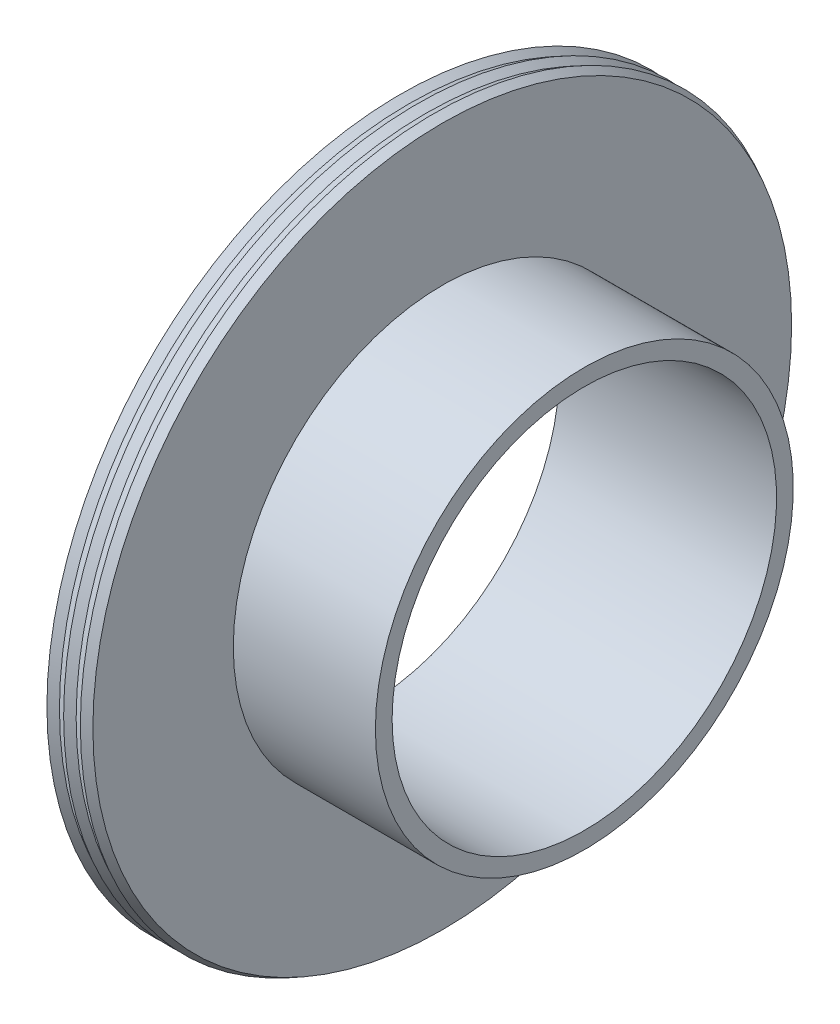
SolidWorks part; units mm, degrees
ref_plane "前视基准面" through (0, 0, 0) normal (0, 0, 1) x (1, 0, 0)
ref_plane "上视基准面" through (0, 0, 0) normal (0, 1, 0) x (1, 0, 0)
ref_plane "右视基准面" through (0, 0, 0) normal (1, 0, 0) x (0, 0, -1)
other "Configuration Table"
sketch "草图1" plane through (0, 0, 0) normal (0, 0, 1) x (1, 0, 0)
  line L0 (-59.6593, 0) -> (89.3294, 0) construction
  line L1 (0, 0) -> (0, 23)
  line L2 (0, 23) -> (26, 23)
  line L3 (26, 23) -> (26, 25)
  line L4 (26, 25) -> (0, 25)
  line L5 (0, 25) -> (0, 23)
  line L6 (0, 0) -> (0, 25)
  line L8 (4, 42.3) -> (9, 42.3)
  line L9 (9, 42.3) -> (9, 25)
  line L10 (9, 25) -> (4, 25)
  line L11 (4, 25) -> (4, 42.3)
  line L13 (4, 42.3) -> (5, 41.8)
  line L14 (5, 41.8) -> (6, 42.3)
  line L15 (6, 42.3) -> (7, 41.8)
  line L16 (7, 41.8) -> (8, 42.3)
  line L17 (8, 42.3) -> (9, 41.8)
  line L19 (9, 41.8) -> (10, 42.3) [skipped]
  dimension "D1" = 23
  dimension "D2" = 2
  dimension "D3" = 26
  dimension "D5" = 17.3
  dimension "D6" = 5
  dimension "D9" = 1
  dimension "D10" = 3
revolve "旋转1" add sketch "草图1" angle 360 about L0
